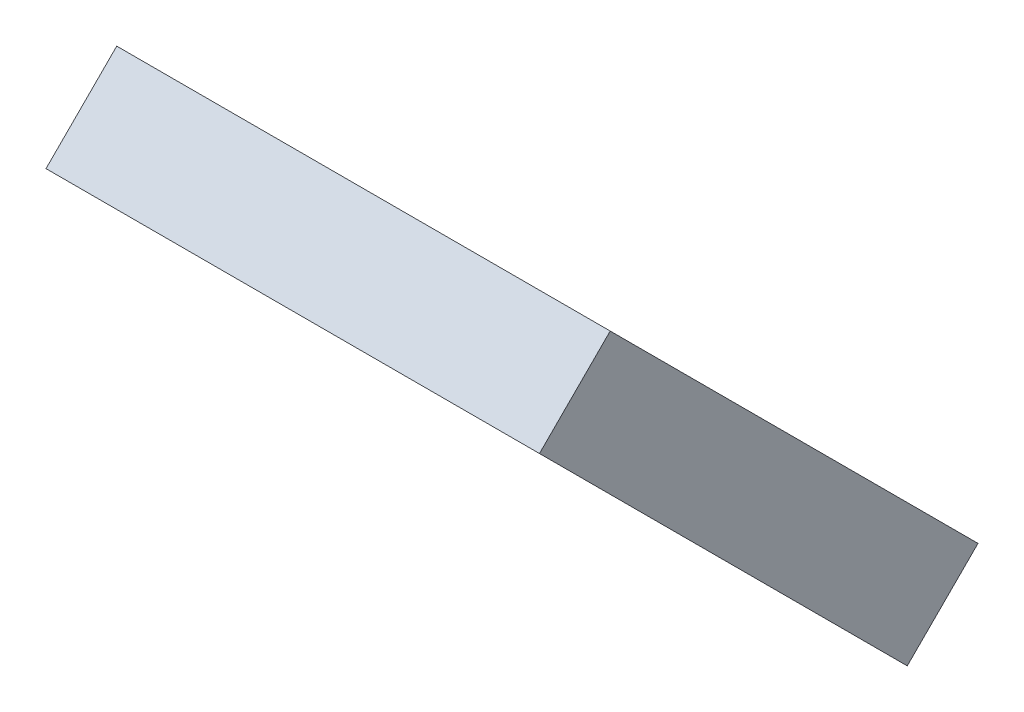
SolidWorks part; units mm, degrees
ref_plane "Front Plane" through (0, 0, 0) normal (0, 0, 1) x (1, 0, 0)
ref_plane "Top Plane" through (0, 0, 0) normal (0, 1, 0) x (1, 0, 0)
ref_plane "Right Plane" through (0, 0, 0) normal (1, 0, 0) x (0, 0, -1)
sketch "Sketch1" plane through (0, -53.8624, 53.8624) normal (0, 0.7071, -0.7071) x (1, 0, 0)
  line L0 (101.8446, -166.8122) -> (45.8446, -166.8122) construction
  line L1 (92.3446, -146.8122) -> (55.3446, -146.8122)
  line L2 (92.3446, -146.8122) -> (92.3446, -107.8122)
  line L3 (92.3446, -107.8122) -> (55.3446, -107.8122)
  line L4 (55.3446, -146.8122) -> (55.3446, -107.8122)
  line L5 (92.3446, -146.8122) -> (55.3446, -107.8122) construction
  line L6 (92.3446, -107.8122) -> (55.3446, -146.8122) construction
  circle A0 centre (88.8446, -143.8122) radius 1.5 construction
  circle A1 centre (58.8446, -143.8122) radius 1.5 construction
  circle A2 centre (58.8446, -110.8122) radius 1.5 construction
  circle A3 centre (88.8446, -110.8122) radius 1.5 construction
  circle A4 centre (88.8446, -143.8122) radius 1.5
  circle A5 centre (58.8446, -143.8122) radius 1.5
  circle A6 centre (58.8446, -110.8122) radius 1.5
  circle A7 centre (88.8446, -110.8122) radius 1.5
  point P0 (73.8446, -127.3122)
  point P5 (73.8446, -166.8122)
  point P8 (73.8446, -146.8122)
  dimension "D1" = 37
  dimension "D2" = 39
  dimension "D3" = 20
extrude "Boss-Extrude1" add sketch "Sketch1" along normal blind 7.5
sketch "Sketch2" plane through (0, -48.5591, 48.5591) normal (0, 0.7071, -0.7071) x (1, 0, 0)
  line L0 (55.3446, -107.8122) -> (55.3446, -146.8122) construction
  line L1 (71.8446, -133.8122) -> (75.8446, -133.8122)
  line L2 (71.8446, -133.8122) -> (71.8446, -128.8122)
  line L3 (71.8446, -128.8122) -> (75.8446, -128.8122)
  line L4 (75.8446, -133.8122) -> (75.8446, -128.8122)
  line L5 (71.8446, -133.8122) -> (75.8446, -128.8122) construction
  line L6 (71.8446, -128.8122) -> (75.8446, -133.8122) construction
  line L7 (55.3446, -146.8122) -> (92.3446, -146.8122) construction
  circle A0 centre (73.8446, -131.3122) radius 2
  point P0 (73.8446, -131.3122)
  dimension "D1" = 18.5
  dimension "D2" = 13
  dimension "D3" = 4
  dimension "D4" = 5
extrude "Cut-Extrude1" cut sketch "Sketch2" against normal through all contours A0
